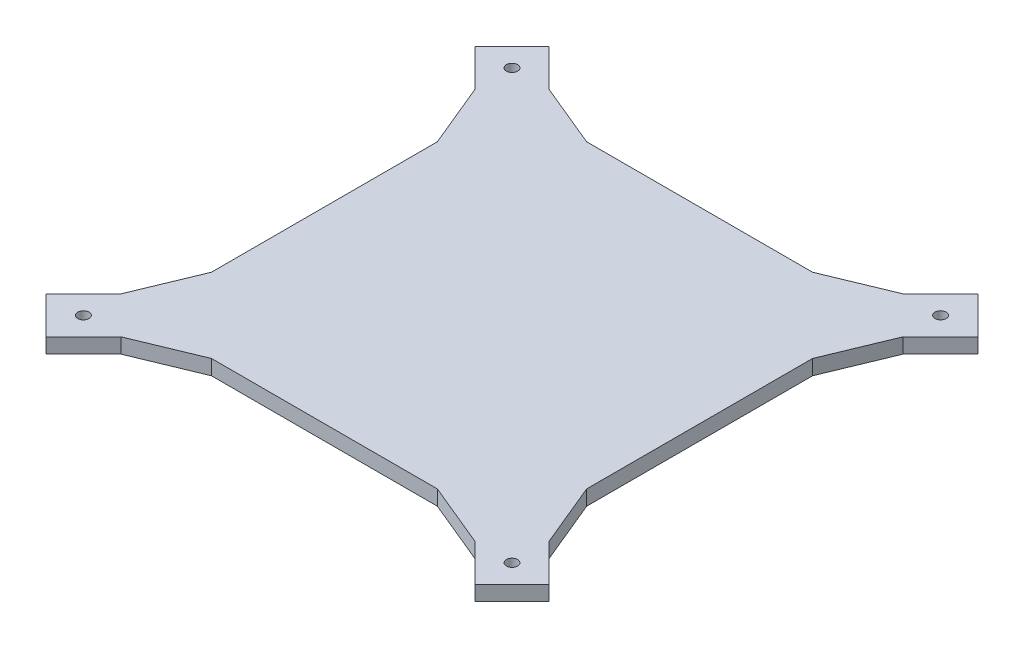
SolidWorks part; units mm, degrees
ref_plane "Front Plane" through (0, 0, 0) normal (0, 0, 1) x (1, 0, 0)
ref_plane "Top Plane" through (0, 0, 0) normal (0, 1, 0) x (1, 0, 0)
ref_plane "Right Plane" through (0, 0, 0) normal (1, 0, 0) x (0, 0, -1)
sketch "Sketch1" plane through (0, 0, 0) normal (0, 1, 0) x (1, 0, 0)
  line L1 (-30.1005, -50) -> (30.1005, -50)
  line L2 (-50, -30.1005) -> (-50, 30.1005)
  line L3 (-30.1005, 50) -> (30.1005, 50)
  line L4 (50, -30.1005) -> (50, 30.1005)
  line L5 (-47.1716, -57.0711) -> (-30.1005, -50)
  line L6 (-50, -30.1005) -> (-57.0711, -47.1716)
  line L7 (-67.0418, -57.1423) -> (-57.1423, -67.0418)
  line L8 (-57.1423, -67.0418) -> (-47.1716, -57.0711)
  line L9 (67.0418, 57.1423) -> (57.1423, 67.0418)
  line L11 (57.1423, 67.0418) -> (47.1716, 57.0711)
  line L12 (47.1716, -57.0711) -> (30.1005, -50)
  line L13 (67.0418, -57.1423) -> (57.1423, -67.0418)
  line L14 (-67.0418, 57.1423) -> (-57.1423, 67.0418)
  line L15 (57.1423, -67.0418) -> (47.1716, -57.0711)
  line L16 (-57.1423, 67.0418) -> (-47.1716, 57.0711)
  line L18 (57.0711, -47.1716) -> (67.0418, -57.1423)
  line L20 (57.0711, 47.1716) -> (67.0418, 57.1423)
  line L22 (-57.0711, 47.1716) -> (-67.0418, 57.1423)
  line L23 (-57.0711, -47.1716) -> (-67.0418, -57.1423)
  line L24 (50, -30.1005) -> (57.0711, -47.1716)
  line L25 (50, 30.1005) -> (57.0711, 47.1716)
  line L26 (47.1716, 57.0711) -> (30.1005, 50)
  line L27 (-47.1716, 57.0711) -> (-30.1005, 50)
  line L28 (-50, 30.1005) -> (-57.0711, 47.1716)
  line L29 (0, -1000) -> (0, 49000) construction
  line L31 (-1000, 0) -> (49000, 0) construction
  circle A0 centre (-57.1067, -57.1067) radius 1.5
  circle A1 centre (-57.1067, 57.1067) radius 1.5
  circle A2 centre (57.1067, -57.1067) radius 1.5
  circle A3 centre (57.1067, 57.1067) radius 1.5
  point P16 (-40.1005, 50)
  point P19 (50, -40.1005)
  point P20 (40.1005, -50)
  point P22 (-50, 40.1005)
  point P23 (40.1005, 50)
  point P24 (50, 40.1005)
  point P26 (-50, -40.1005)
  point P27 (-40.1005, -50)
  point P45 (0, 0)
  dimension "D2" = 3
  dimension "D7" = 14.1007
  dimension "D11" = 14
extrude "Boss-Extrude2" add sketch "Sketch1" along normal blind 4
sketch "Sketch2" plane through (0, 4, 0) normal (0, 1, 0) x (1, 0, 0)
